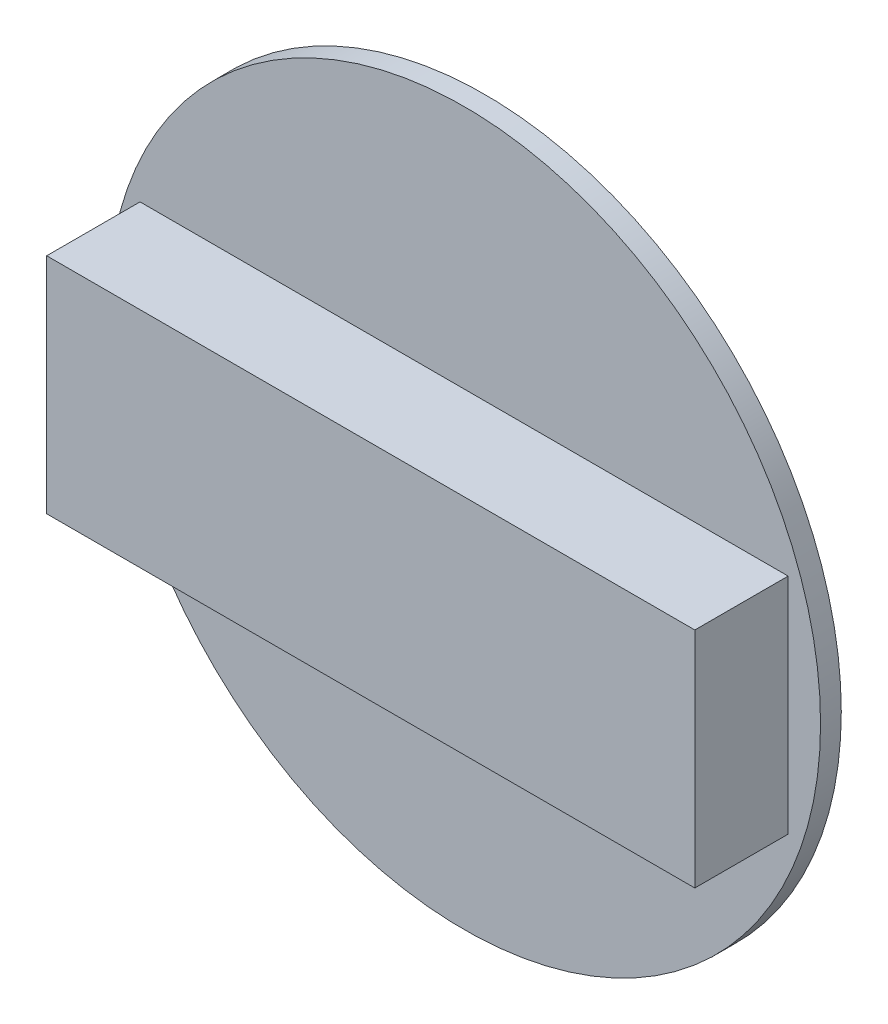
SolidWorks part; units mm, degrees
ref_plane "前视基准面" through (0, 0, 0) normal (0, 0, 1) x (1, 0, 0)
ref_plane "上视基准面" through (0, 0, 0) normal (0, 1, 0) x (1, 0, 0)
ref_plane "右视基准面" through (0, 0, 0) normal (1, 0, 0) x (0, 0, -1)
other "Configuration Table"
sketch "草图1" plane through (0, 0, 0) normal (0, 0, 1) x (1, 0, 0)
  circle A0 centre (0, 0) radius 27.5
  dimension "D1" = 55
extrude "凸台-拉伸1" add sketch "草图1" along normal blind 1.6
sketch "草图2" plane through (0, 0, 1.6) normal (0, 0, 1) x (1, 0, 0)
  line L1 (-25, -8.62) -> (25, -8.62)
  line L2 (-25, -8.62) -> (-25, 8.62)
  line L3 (-25, 8.62) -> (25, 8.62)
  line L4 (25, -8.62) -> (25, 8.62)
  line L5 (-25, -8.62) -> (25, 8.62) construction
  line L6 (-25, 8.62) -> (25, -8.62) construction
  point P0 (0, 0)
  dimension "D1" = 50
  dimension "D2" = 17.24
extrude "凸台-拉伸2" add sketch "草图2" along normal blind 7.2
sketch "草图3" plane through (0, 0, 1.6) normal (0, 0, 1) x (1, 0, 0)
  line L0 (0, 0) -> (-27.5, 0) construction
  line L1 (-27.4431, 1.7678) -> (-26.3825, 0.7071)
  line L2 (-27.4431, -1.7678) -> (-26.3825, -0.7071)
  arc A1 (-26.3825, -0.7071) -> (-26.3825, 0.7071) centre (-27.0896, 0) ccw
  circle A2 centre (0, 0) radius 27.5
  arc A5 (-27.4431, 1.7678) -> (-27.4431, -1.7678) centre (0, 0) ccw
  point P7 (0, 0)
  point P10 (-25.6754, 0)
  dimension "D1" = 0
  dimension "D2" = 45
  dimension "D4" = 1
  dimension "D3" = 2.5
extrude "切除-拉伸1" cut sketch "草图3" against normal through all
sketch "草图4" plane through (0, 0, 0) normal (0, 0, -1) x (-1, 0, 0)
  line L2 (26.3825, 0.7071) -> (27.4431, 1.7678)
  line L3 (27.4431, -1.7678) -> (26.3825, -0.7071)
  line L4 (26.3825, 0.7071) -> (27.4431, 1.7678)
  line L5 (27.4431, -1.7678) -> (26.3825, -0.7071)
  arc A2 (26.3825, 0.7071) -> (26.3825, -0.7071) centre (27.0896, 0) ccw
  arc A3 (27.4431, 1.7678) -> (27.4431, -1.7678) centre (0, 0) ccw
  arc A4 (26.3825, 0.7071) -> (26.3825, -0.7071) centre (27.0896, 0) ccw
  arc A5 (27.4431, 1.7678) -> (27.4431, -1.7678) centre (0, 0) ccw
  dimension "D1" = 0
